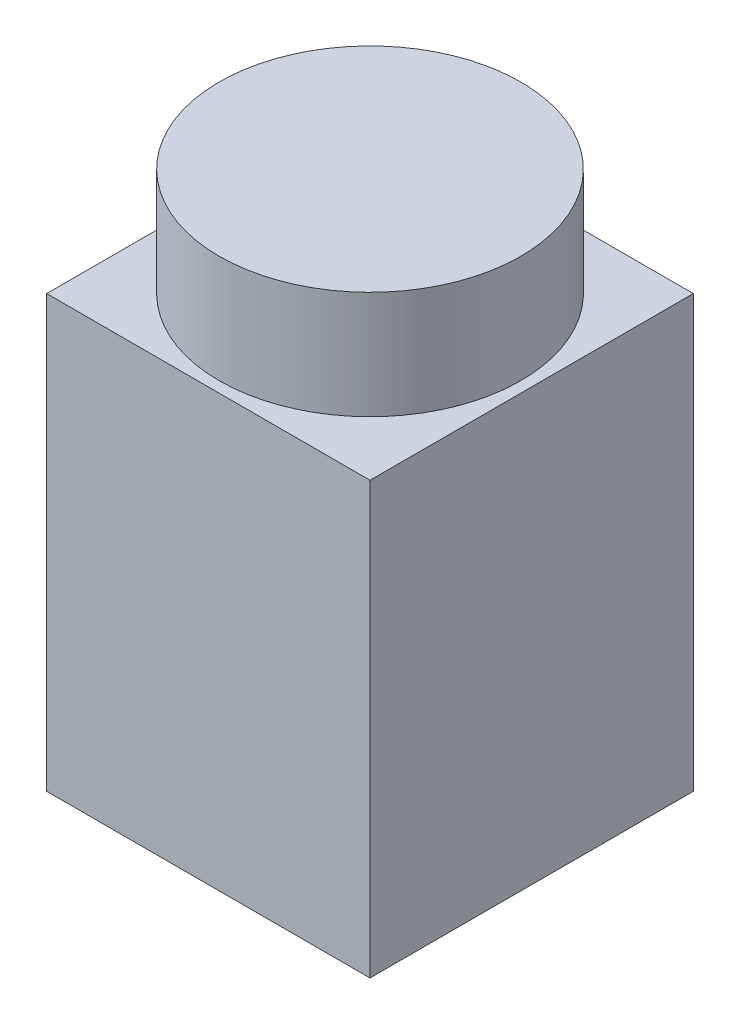
SolidWorks part; units mm, degrees
ref_plane "Front Plane" through (0, 0, 0) normal (0, 0, 1) x (1, 0, 0)
ref_plane "Top Plane" through (0, 0, 0) normal (0, 1, 0) x (1, 0, 0)
ref_plane "Right Plane" through (0, 0, 0) normal (1, 0, 0) x (0, 0, -1)
sketch "Sketch1" plane through (0, 0, 0) normal (0, 1, 0) x (1, 0, 0)
  line L1 (0, 0) -> (30, 0)
  line L2 (0, 0) -> (0, 30)
  line L3 (0, 30) -> (30, 30)
  line L4 (30, 0) -> (30, 30)
  dimension "D1" = 30
  dimension "D2" = 30
extrude "Boss-Extrude1" add sketch "Sketch1" along normal blind 40
sketch "Sketch2" plane through (0, 40, 0) normal (0, 1, 0) x (1, 0, 0)
  line L0 (0, 30) -> (30, 0) construction
  circle A0 centre (15, 15) radius 14
  dimension "D1" = 28
extrude "Boss-Extrude2" add sketch "Sketch2" along normal blind 10
